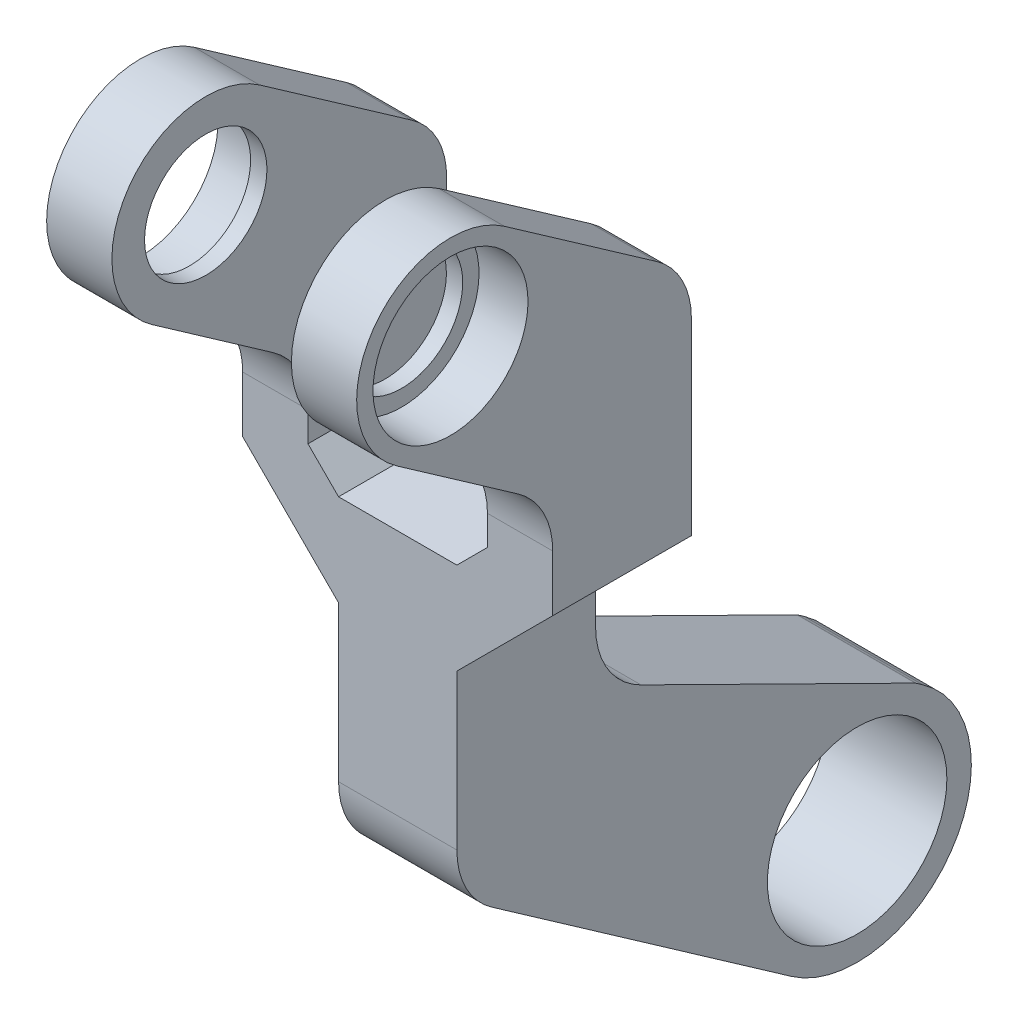
SolidWorks part; units mm, degrees
ref_plane "前视基准面" through (0, 0, 0) normal (0, 0, 1) x (1, 0, 0)
ref_plane "上视基准面" through (0, 0, 0) normal (0, 1, 0) x (1, 0, 0)
ref_plane "右视基准面" through (0, 0, 0) normal (1, 0, 0) x (0, 0, -1)
sketch "草图1" plane through (0, 0, 0) normal (0, 0, 1) x (1, 0, 0)
  line L0 (0, 0) -> (14.5, 0)
  line L1 (14.5, 0) -> (14.5, 20)
  line L2 (14.5, 20) -> (26.25, 31.75)
  line L3 (26.25, 31.75) -> (26.25, 60)
  line L4 (26.25, 60) -> (18.25, 60)
  line L5 (18.25, 60) -> (18.25, 35)
  line L6 (18.25, 35) -> (-3.75, 35)
  line L7 (-3.75, 35) -> (-3.75, 60)
  line L8 (-3.75, 60) -> (-11.75, 60)
  line L9 (-11.75, 60) -> (-11.75, 31.75)
  line L11 (0, 20) -> (0, 0)
  line L12 (0, 20) -> (-11.75, 31.75)
  line L13 (7.25, 0) -> (7.25, 20.1674) construction
  dimension "D1" = 135
  dimension "D2" = 135
  dimension "D3" = 14.5
  dimension "D4" = 8
  dimension "D5" = 8
  dimension "D6" = 22
  dimension "D7" = 60
  dimension "D8" = 20
  dimension "D9" = 25
extrude "凸台-拉伸1" add sketch "草图1" along normal blind 23
sketch "草图2" plane through (0, 0, 23) normal (0, 0, 1) x (1, 0, 0)
  line L0 (-3.75, 35) -> (0, 31.25)
  line L1 (0, 31.25) -> (14.5, 31.25)
  line L2 (14.5, 31.25) -> (18.25, 35)
  line L3 (-11.75, 31.75) -> (0, 20) construction
  line L4 (14.5, 20) -> (26.25, 31.75) construction
  line L5 (-3.75, 35) -> (18.25, 35)
extrude "切除-拉伸1" cut sketch "草图2" against normal through all
sketch "草图3" plane through (14.5, 0, 0) normal (1, 0, 0) x (0, 0, -1)
  line L0 (-23, 0) -> (0, 0)
  arc A0 (-23, 0) -> (0, 0) centre (-11.5, 0) ccw
extrude "凸台-拉伸2" [suppressed] add sketch "草图3" against normal up to surface (14.5 mm away)
sketch "草图4" [suppressed] plane through (14.5, 0, 0) normal (1, 0, 0) x (0, 0, -1)
  circle A0 centre (-11.5, 0) radius 7.5
  dimension "D1" = 15
extrude "切除-拉伸2" [suppressed] cut sketch "草图4" against normal blind 20
sketch "草图5" [suppressed] plane through (14.5, 0, 0) normal (1, 0, 0) x (0, 0, -1)
  circle A0 centre (-11.5, 0) radius 9.5
  dimension "D1" = 19
extrude "切除-拉伸3" [suppressed] cut sketch "草图5" against normal blind 6
sketch "草图6" [suppressed] plane through (0, 0, 0) normal (-1, 0, 0) x (0, 0, 1)
  circle A0 centre (11.5, 0) radius 9.5
  dimension "D1" = 19
extrude "切除-拉伸4" [suppressed] cut sketch "草图6" against normal blind 6
sketch "草图7" plane through (26.25, 0, 0) normal (1, 0, 0) x (0, 0, -1)
  line L0 (-23, 60) -> (0, 60)
  arc A0 (-23, 60) -> (0, 60) centre (-11.5, 60) cw
extrude "凸台-拉伸3" [suppressed] add sketch "草图7" against normal up to surface (8 mm away)
sketch "草图8" [suppressed] plane through (-11.75, 0, 0) normal (-1, 0, 0) x (0, 0, 1)
  line L0 (0, 55) -> (23, 55)
  arc A0 (0, 55) -> (23, 55) centre (11.5, 55) cw
extrude "凸台-拉伸4" [suppressed] add sketch "草图8" against normal up to surface (8 mm away)
sketch "草图15" plane through (26.25, 0, 0) normal (1, 0, 0) x (0, 0, -1)
  line L0 (0, 60) -> (-22.9363, 76.0601)
  line L1 (-22.9363, 76.0601) -> (-36.1285, 57.2196)
  line L2 (-36.1285, 57.2196) -> (-23, 48.027)
  line L3 (-23, 31.75) -> (-23, 60) construction
  line L4 (-23, 48.027) -> (0, 60)
  dimension "D1" = 23
  dimension "D2" = 125
  dimension "D3" = 28
extrude "凸台-拉伸7" add sketch "草图15" against normal up to surface (38 mm away) up to face at (-11.75, 45.875, 11.5)
sketch "草图17" plane through (26.25, 0, 0) normal (1, 0, 0) x (0, 0, -1)
  line L0 (-22.9363, 76.0601) -> (-36.1285, 57.2196)
  arc A0 (-22.9363, 76.0601) -> (-36.1285, 57.2196) centre (-29.5324, 66.6399) ccw
extrude "凸台-拉伸8" add sketch "草图17" against normal up to surface (38 mm away) up to face at (-11.75, 50.8011, 17.5108)
sketch "草图18" plane through (26.25, 0, 0) normal (1, 0, 0) x (0, 0, -1)
  circle A0 centre (-29.5324, 66.6399) radius 7.5
  dimension "D1" = 15
extrude "切除-拉伸10" cut sketch "草图18" against normal through all
sketch "草图16" plane through (0, 47.2073, 24.5746) normal (0, -0.887, -0.4617) x (1, 0, 0)
  line L1 (-3.75, -27.7049) -> (18.25, -27.7049)
  line L2 (-3.75, -27.7049) -> (-3.75, 77.5693)
  line L3 (-3.75, 77.5693) -> (18.25, 77.5693)
  line L4 (18.25, -27.7049) -> (18.25, 77.5693)
extrude "切除-拉伸9" cut sketch "草图16" against normal through all
sketch "草图9" [suppressed] plane through (-11.75, 0, 0) normal (-1, 0, 0) x (0, 0, 1)
  circle A0 centre (11.5, 55) radius 7.5
  dimension "D1" = 15
extrude "切除-拉伸5" [suppressed] cut sketch "草图9" against normal blind 62
sketch "草图10" [suppressed] plane through (-11.75, 0, 0) normal (-1, 0, 0) x (0, 0, 1)
  circle A0 centre (11.5, 55) radius 9.5
  dimension "D1" = 19
extrude "切除-拉伸6" [suppressed] cut sketch "草图10" against normal blind 6
sketch "草图11" [suppressed] plane through (26.25, 0, 0) normal (1, 0, 0) x (0, 0, -1)
  circle A0 centre (-11.5, 55) radius 9.5
  dimension "D1" = 19
extrude "切除-拉伸7" [suppressed] cut sketch "草图11" against normal blind 6
sketch "草图12" plane through (14.5, 0, 0) normal (1, 0, 0) x (0, 0, -1)
  line L0 (0, 18.0769) -> (40.0924, -9.9961)
  line L1 (0, 0) -> (0, 20) construction
  line L2 (-23, 0) -> (24.0323, -32.9324)
  line L3 (-23, 0) -> (-23, 20) construction
  line L4 (40.0924, -9.9961) -> (24.0323, -32.9324)
  line L5 (-23, 0) -> (0, 18.0769)
  line L6 (0, 20) -> (0, 0) construction
  circle A0 centre (-29.5324, 66.6399) radius 7.5 construction
  point P7 (32.0624, -21.4642)
  dimension "D1" = 235
  dimension "D2" = 28
  dimension "D3" = 107.5
extrude "凸台-拉伸5" add sketch "草图12" against normal up to surface (14.5 mm away) up to face at (0, 10, 11.5)
sketch "草图13" plane through (14.5, 0, 0) normal (1, 0, 0) x (0, 0, -1)
  line L0 (40.0924, -9.9961) -> (24.0323, -32.9324)
  arc A0 (40.0924, -9.9961) -> (24.0323, -32.9324) centre (32.0624, -21.4642) cw
extrude "凸台-拉伸6" add sketch "草图13" against normal up to surface (14.5 mm away) up to face at (0, 2.5247, -3.0208)
sketch "草图14" plane through (14.5, 0, 0) normal (1, 0, 0) x (0, 0, -1)
  circle A0 centre (32.0624, -21.4642) radius 11
  dimension "D1" = 22
extrude "切除-拉伸8" cut sketch "草图14" against normal up to surface (14.5 mm away) up to face at (0, 1.1864, -4.9321)
sketch "草图19" plane through (26.25, 0, 0) normal (1, 0, 0) x (0, 0, -1)
  circle A0 centre (-29.5324, 66.6399) radius 9.5
  dimension "D1" = 19
extrude "切除-拉伸11" cut sketch "草图19" against normal blind 6
sketch "草图20" plane through (-11.75, 0, 0) normal (-1, 0, 0) x (0, 0, 1)
  circle A0 centre (29.5324, 66.6399) radius 9.5
  dimension "D1" = 19
extrude "切除-拉伸12" cut sketch "草图20" against normal blind 6
sketch "草图21" plane through (26.25, 0, 0) normal (1, 0, 0) x (0, 0, -1)
  line L0 (-23, 48.027) -> (-17, 43.8257)
  line L1 (-17, 43.8257) -> (-17, -13.1673)
  line L2 (-17, -13.1673) -> (-41.8543, 0)
  line L3 (-41.8543, 0) -> (-23, 48.027)
  line L4 (-36.1285, 57.2196) -> (-23, 48.027) construction
  line L5 (0, 31.75) -> (0, 60) construction
  dimension "D1" = 17
extrude "切除-拉伸13" cut sketch "草图21" against normal blind 42
sketch "草图22" plane through (14.5, 0, 0) normal (1, 0, 0) x (0, 0, -1)
  line L0 (0, 18.0769) -> (0, 10)
  line L1 (0, 10) -> (39.1954, -9.3731)
  line L2 (0, 18.0769) -> (51.6383, -1.3119)
  line L3 (51.6383, -1.3119) -> (44.6995, -15.3504)
  arc A0 (24.0323, -32.9324) -> (40.0924, -9.9961) centre (32.0624, -21.4642) ccw construction
  arc A1 (44.6995, -15.3504) -> (39.1954, -9.3731) centre (32.0624, -21.4642) ccw
  dimension "D1" = 50
extrude "切除-拉伸14" cut sketch "草图22" against normal blind 42
fillet "圆角1" radius 10 6 edges at (-7.75, 60, 0) (22.25, 60, 0) (22.25, 43.8257, 17) (-7.75, 43.8257, 17) (7.25, 10, 0) (7.25, -4.2012, 17)
